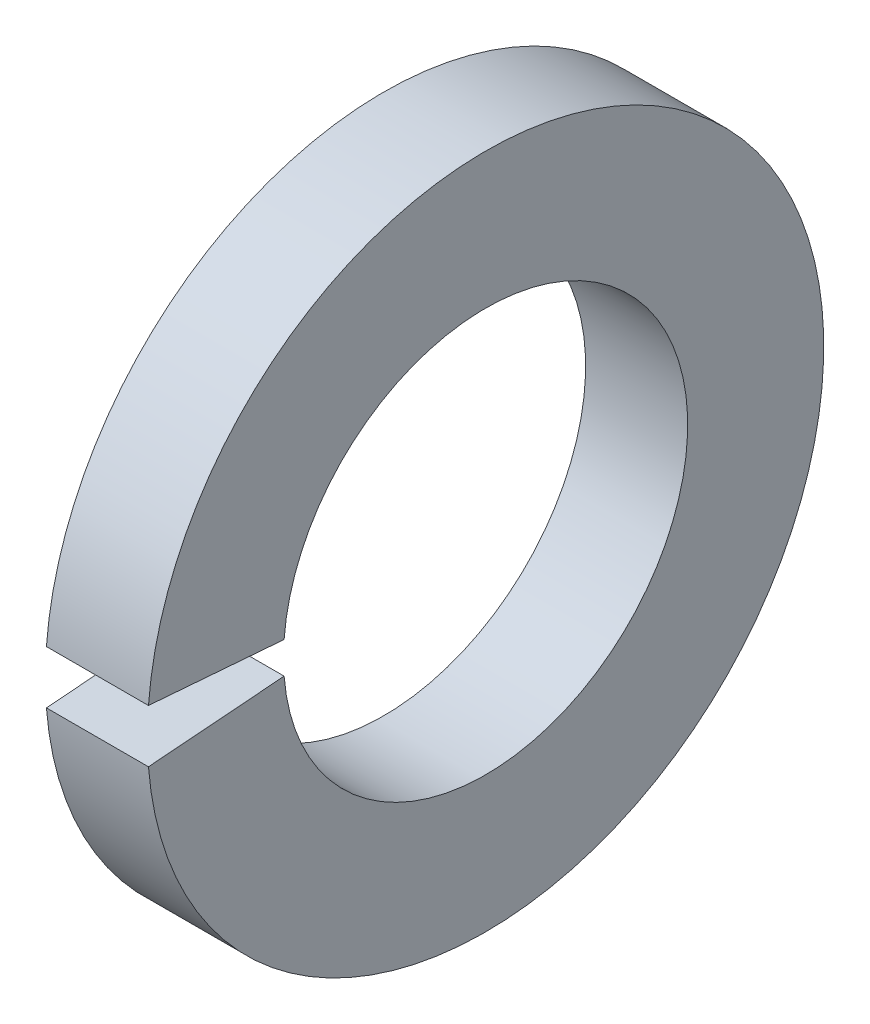
SolidWorks part; units mm, degrees
ref_plane "Plane1" through (0, 0, 0) normal (0, 0, 1) x (1, 0, 0)
ref_plane "Plane2" through (0, 0, 0) normal (0, 1, 0) x (1, 0, 0)
ref_plane "Plane3" through (0, 0, 0) normal (1, 0, 0) x (0, 0, -1)
sketch "Sketch1" plane through (0, 0, 0) normal (0, 0, 1) x (1, 0, 0)
  line L0 (-34.925, 0) -> (9.525, 0) construction
  line L1 (0, 10.1) -> (0, 16.9)
  line L2 (0, 16.9) -> (-5.1, 16.9)
  line L3 (-5.1, 16.9) -> (-5.1, 10.1)
  line L4 (-5.1, 10.1) -> (0, 10.1)
  dimension "Thickness" = 5.1
  dimension "Inside_dia" = 20.2
  dimension "Outside_dia" = 33.8
revolve "Base-Revolve" add sketch "Sketch1" angle 360 about L0
sketch "Sketch2" plane through (0, 0, 0) normal (-1, 0, 0) x (0, -1, 0)
  line L0 (0, 0) -> (1.3525, 17.1849)
  line L1 (0, -3.175) -> (0, 12.7) construction
  line L2 (0, 0) -> (-1.3525, 17.1849)
  arc A0 (1.3525, 17.1849) -> (-1.3525, 17.1849) centre (0, 0) ccw
  dimension "Gap_ang" = 9
  dimension "D1" = 17.238
extrude "Gap" cut sketch "Sketch2" along normal through all
equation "\"D1@Sketch2\" = \"Outside_dia@Sketch1\" * 0.51"
